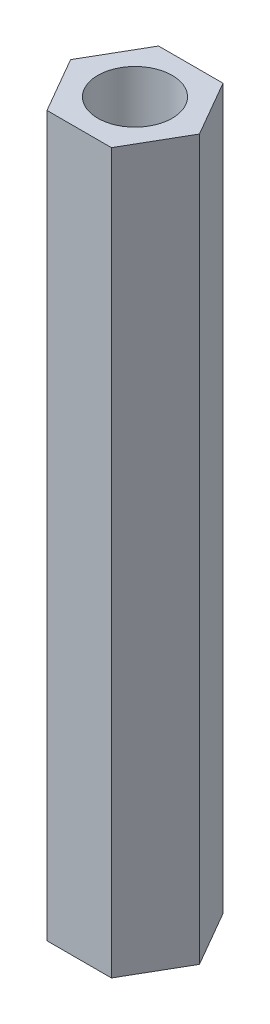
SolidWorks part; units mm, degrees
material "高铅黄铜，UNS C34200"
ref_plane "前视基准面" through (0, 0, 0) normal (0, 0, 1) x (1, 0, 0)
ref_plane "上视基准面" through (0, 0, 0) normal (0, 1, 0) x (1, 0, 0)
ref_plane "右视基准面" through (0, 0, 0) normal (1, 0, 0) x (0, 0, -1)
sketch "草图1" plane through (0, 0, 0) normal (0, 1, 0) x (1, 0, 0)
  line L1 (5.1962, 0) -> (2.5981, 4.5)
  line L2 (2.5981, 4.5) -> (-2.5981, 4.5)
  line L3 (-2.5981, 4.5) -> (-5.1962, 0)
  line L4 (-5.1962, 0) -> (-2.5981, -4.5)
  line L5 (-2.5981, -4.5) -> (2.5981, -4.5)
  line L6 (2.5981, -4.5) -> (5.1962, 0)
  circle A0 centre (0, 0) radius 3
  circle A1 centre (0, 0) radius 4.5 construction
extrude "凸台-拉伸1" add sketch "草图1" along normal blind 58
